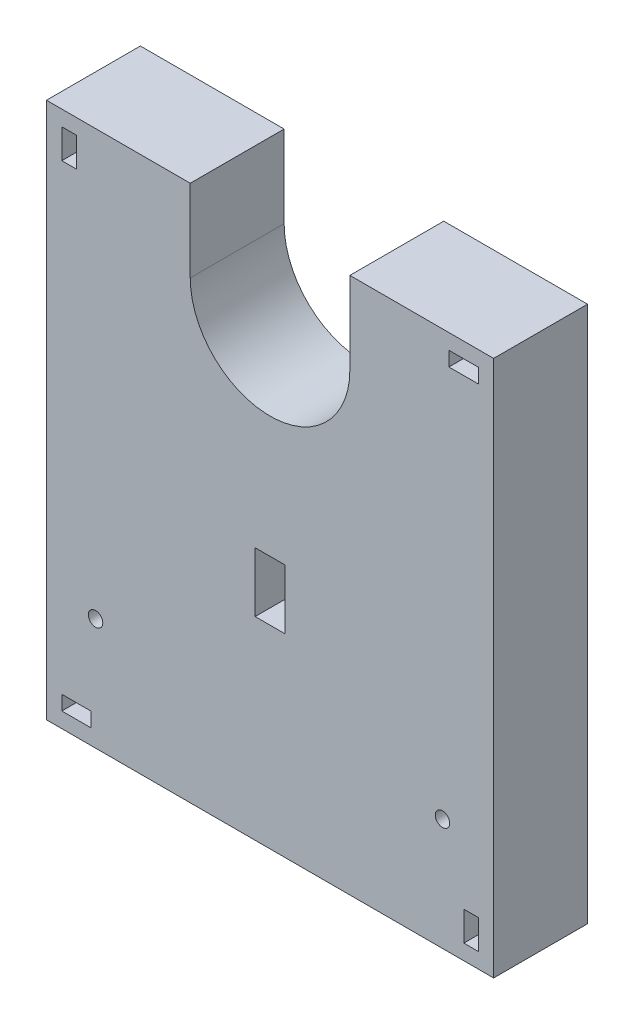
SolidWorks part; units mm, degrees
ref_plane "Front" through (0, 0, 0) normal (0, 0, 1) x (1, 0, 0)
ref_plane "Top" through (0, 0, 0) normal (0, 1, 0) x (1, 0, 0)
ref_plane "Right" through (0, 0, 0) normal (1, 0, 0) x (0, 0, -1)
sketch "Sketch1" plane through (0, 0, 0) normal (0, 0, 1) x (1, 0, 0)
  line L0 (0, 0) -> (95.25, 0)
  line L1 (0, 0) -> (0, 114.3)
  line L2 (0, 114.3) -> (30.625, 114.3)
  line L3 (95.25, 114.3) -> (95.25, 0)
  line L4 (47.625, 114.3) -> (47.625, 0) construction
  line L5 (0, 57.15) -> (95.25, 57.15) construction
  line L6 (3.2639, 3.2639) -> (9.525, 3.2639)
  line L7 (3.2639, 3.2639) -> (3.2639, 6.35)
  line L8 (9.525, 6.35) -> (9.525, 3.2639)
  line L9 (9.525, 6.35) -> (3.2639, 6.35)
  line L10 (47.625, 53.975) -> (47.625, 41.275) construction
  line L11 (50.8, 41.275) -> (44.45, 41.275)
  line L12 (88.9, 9.525) -> (91.9861, 9.525)
  line L13 (88.9, 9.525) -> (88.9, 3.2639)
  line L14 (91.9861, 3.2639) -> (91.9861, 9.525)
  line L15 (91.9861, 3.2639) -> (88.9, 3.2639)
  line L16 (6.35, 104.775) -> (3.2639, 104.775)
  line L17 (6.35, 104.775) -> (6.35, 111.0361)
  line L18 (3.2639, 111.0361) -> (3.2639, 104.775)
  line L19 (3.2639, 111.0361) -> (6.35, 111.0361)
  line L20 (91.9861, 111.0361) -> (85.725, 111.0361)
  line L21 (91.9861, 111.0361) -> (91.9861, 107.95)
  line L22 (85.725, 107.95) -> (85.725, 111.0361)
  line L23 (85.725, 107.95) -> (91.9861, 107.95)
  line L24 (44.45, 41.275) -> (44.45, 53.975)
  line L25 (44.45, 53.975) -> (50.8, 53.975)
  line L26 (50.8, 53.975) -> (50.8, 41.275)
  line L27 (30.625, 96.8375) -> (30.625, 114.3)
  line L28 (64.625, 96.8375) -> (64.625, 114.3)
  line L29 (64.625, 114.3) -> (95.25, 114.3)
  circle A0 centre (84.348, 23.8529) radius 1.5367
  circle A1 centre (10.4583, 23.8529) radius 1.5378
  arc A2 (30.625, 96.8375) -> (64.625, 96.8375) centre (47.625, 96.8375) ccw
  dimension "D1" = 12.7
  dimension "D9" = 10.4583
  dimension "D10" = 23.8529
  dimension "D11" = 3.0756
  dimension "D12" = 10.902
  dimension "D13" = 23.8529
  dimension "D14" = 3.0734
  dimension "D16" = 17
  dimension "D17" = 17.4625
  dimension "D2" = 6.35
  dimension "D3" = 95.25
  dimension "D4" = 114.3
  dimension "D5" = 3.0861
  dimension "D6" = 6.2611
  dimension "D7" = 3.2639
  dimension "D8" = 3.2639
  dimension "D15" = 3.175
  dimension "D18" = 34
  dimension "D19" = 3.2639
  dimension "D20" = 3.2639
  dimension "D21" = 6.2611
  dimension "D22" = 3.0861
  dimension "D23" = 6.2611
  dimension "D24" = 3.0861
  dimension "D25" = 3.2639
  dimension "D26" = 3.2639
  dimension "D27" = 3.0861
  dimension "D28" = 6.2611
  dimension "D29" = 6.2611
  dimension "D30" = 3.0861
  dimension "D31" = 6.2611
  dimension "D32" = 3.0861
  dimension "D33" = 6.2611
  dimension "D34" = 3.0861
  dimension "D35" = 3.2639
  dimension "D36" = 3.2639
extrude "Boss-Extrude5" add sketch "Sketch1" along normal blind 20
